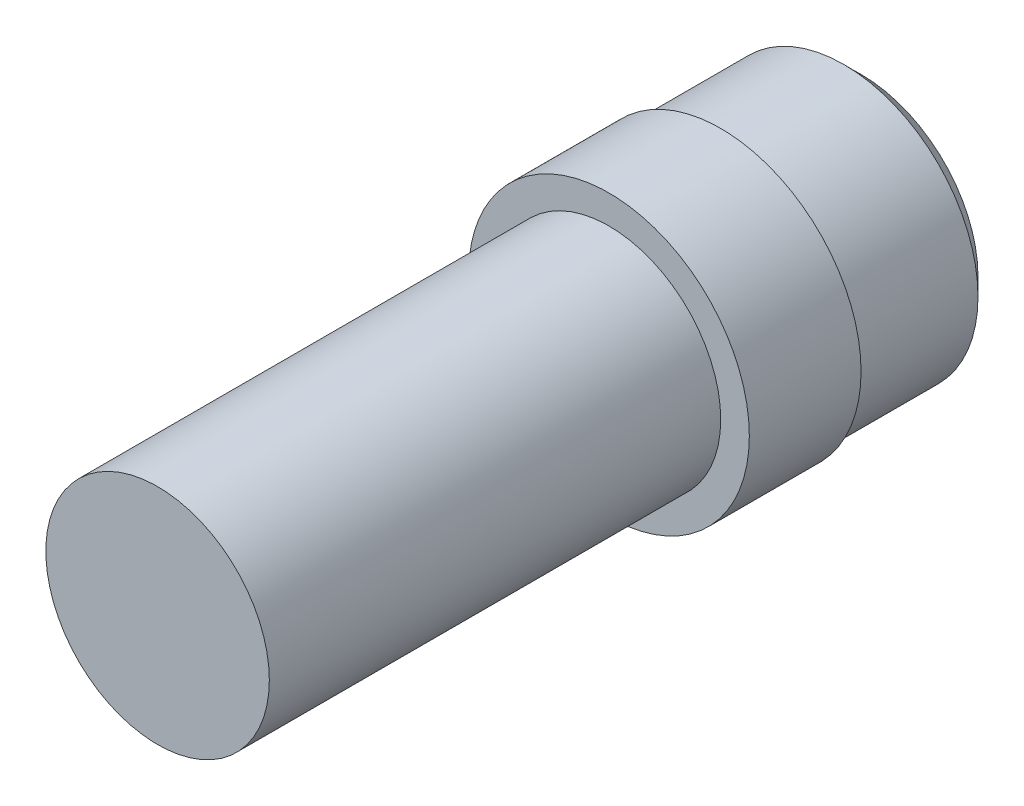
SolidWorks part; units mm, degrees
material "ABS"
ref_plane "Ground_Plane" through (0, 0, 0) normal (0, 0, 1) x (1, 0, 0)
ref_plane "VehicleCentre_Plane" through (0, 0, 0) normal (0, 1, 0) x (1, 0, 0)
ref_plane "FrontAxle_Plane" through (0, 0, 0) normal (1, 0, 0) x (0, 0, -1)
sketch "Sketch1" plane through (0, 0, 0) normal (0, 1, 0) x (1, 0, 0)
  line L0 (3.175, -20) -> (0, -20)
  line L1 (0, -20) -> (0, 0)
  line L2 (0, 0) -> (3.81, 0)
  line L3 (3.81, 0) -> (3.81, -4)
  line L4 (3.81, -4) -> (3.9878, -4)
  line L5 (3.9878, -4) -> (3.9878, -7.175)
  line L6 (3.9878, -7.175) -> (3.175, -7.175)
  line L7 (3.175, -7.175) -> (3.175, -20)
  dimension "D1" = 4
  dimension "D2" = 3.175
  dimension "D3" = 3.9878
  dimension "D4" = 3.81
  dimension "D5" = 3.175
  dimension "D6" = 20
revolve "Revolve1" add sketch "Sketch1" angle 360 about L1
chamfer "Chamfer1" distance 0.5 angle 45 1 edges at (3.81, 0, 0)
